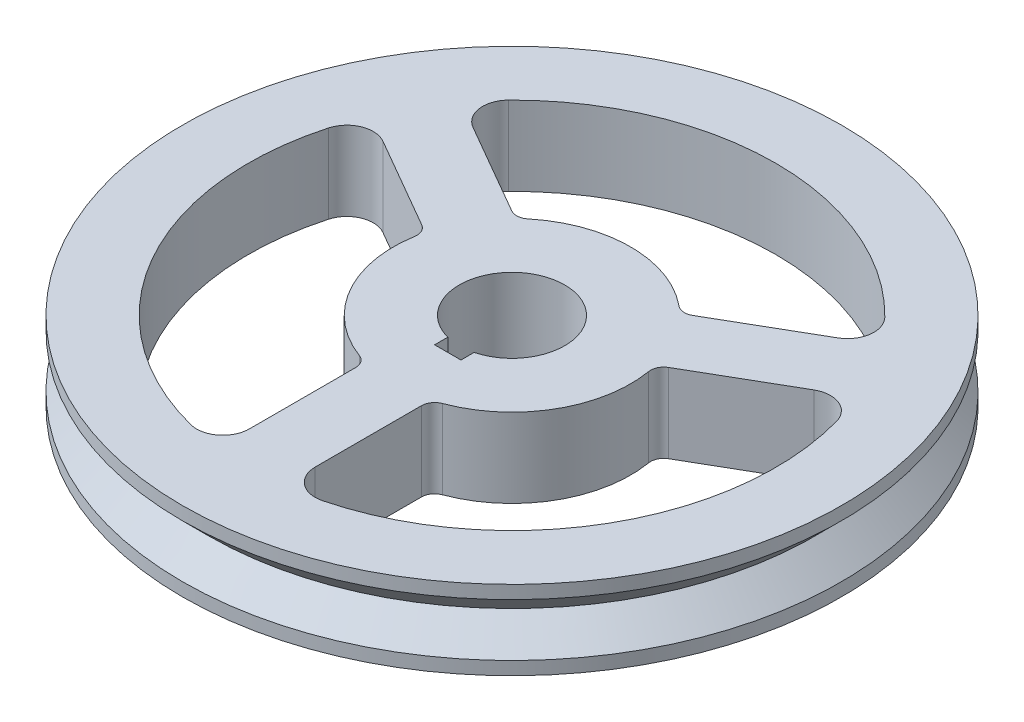
SolidWorks part; units mm, degrees
ref_plane "Front Plane" through (0, 0, 0) normal (0, 0, 1) x (1, 0, 0)
ref_plane "Top Plane" through (0, 0, 0) normal (0, 1, 0) x (1, 0, 0)
ref_plane "Right Plane" through (0, 0, 0) normal (1, 0, 0) x (0, 0, -1)
sketch "Sketch1" plane through (0, 0, 0) normal (0, 1, 0) x (1, 0, 0)
  line L0 (0, 185.3703) -> (0, -173.0817) construction
  line L1 (-213.9236, 0) -> (226.8817, 0) construction
  line L2 (34.3125, 34.2441) -> (69.2173, 54.3964)
  line L3 (0, 0) -> (-86.6025, 50) construction
  line L4 (-12.5, -46.8375) -> (-12.5, -87.1421)
  line L6 (-46.8125, 12.5934) -> (-81.7173, 32.7457)
  line L7 (-34.3125, 34.2441) -> (-69.2173, 54.3964)
  line L8 (12.5, -46.8375) -> (12.5, -87.1421)
  line L9 (46.8125, 12.5934) -> (81.7173, 32.7457)
  line L10 (-5, -19.3649) -> (-5, -24.3649)
  line L11 (5, -19.3649) -> (5, -24.3649)
  line L12 (-5, -24.3649) -> (5, -24.3649)
  circle A0 centre (0, 0) radius 125
  arc A1 (-96.3525, 26.7617) -> (-25, -96.8246) centre (0, 0) ccw
  arc A2 (-44.3812, 7.437) -> (-15.75, -42.1537) centre (0, 0) ccw
  arc A5 (-12.5, -87.1421) -> (-25, -96.8246) centre (-22.5, -87.1421) cw
  arc A6 (-81.7173, 32.7457) -> (-96.3525, 26.7617) centre (-86.7173, 24.0855) ccw
  arc A7 (-12.5, -46.8375) -> (-15.75, -42.1537) centre (-17.5, -46.8375) ccw
  arc A8 (-46.8125, 12.5934) -> (-44.3812, 7.437) centre (-49.3125, 8.2633) cw
  arc A9 (34.3125, 34.2441) -> (28.6312, 34.7168) centre (31.8125, 38.5742) cw
  arc A10 (69.2173, 54.3964) -> (71.3525, 70.0629) centre (64.2173, 63.0566) ccw
  arc A11 (71.3525, 70.0629) -> (-71.3525, 70.0629) centre (0, 0) ccw
  arc A12 (-69.2173, 54.3964) -> (-71.3525, 70.0629) centre (-64.2173, 63.0566) cw
  arc A13 (-34.3125, 34.2441) -> (-28.6312, 34.7168) centre (-31.8125, 38.5742) ccw
  arc A14 (28.6312, 34.7168) -> (-28.6312, 34.7168) centre (0, 0) ccw
  arc A15 (12.5, -46.8375) -> (15.75, -42.1537) centre (17.5, -46.8375) cw
  arc A16 (12.5, -87.1421) -> (25, -96.8246) centre (22.5, -87.1421) ccw
  arc A17 (25, -96.8246) -> (96.3525, 26.7617) centre (0, 0) ccw
  arc A18 (81.7173, 32.7457) -> (96.3525, 26.7617) centre (86.7173, 24.0855) cw
  arc A19 (46.8125, 12.5934) -> (44.3812, 7.437) centre (49.3125, 8.2633) ccw
  arc A20 (15.75, -42.1537) -> (44.3812, 7.437) centre (0, 0) ccw
  arc A21 (5, -19.3649) -> (-5, -19.3649) centre (0, 0) ccw
  point P17 (-12.5, -99.2157)
  point P22 (-92.1733, 38.7825)
  point P27 (-43.6874, 10.7892)
  point P49 (0, 0)
  dimension "D1" = 250
  dimension "D2" = 100
  dimension "D3" = 45
  dimension "D8" = 10
  dimension "D9" = 5
  dimension "D10" = 40
  dimension "D4" = 25
  dimension "D5" = 120
  dimension "D6" = 25
  dimension "D7" = 3
  dimension "D11" = 10
  dimension "D12" = 5
extrude "Boss-Extrude1" add sketch "Sketch1" along normal mid plane 30
sketch "Sketch2" plane through (0, 0, 0) normal (0, 0, 1) x (1, 0, 0)
  line L0 (-125, 10) -> (-125, -10)
  line L1 (-125, 10) -> (-115, 0)
  line L2 (-115, 0) -> (-125, -10)
  line L3 (125, 15) -> (-125, 15) construction
  line L4 (-125, -15) -> (125, -15) construction
  line L5 (0, 35.4267) -> (0, -44.7474) construction
  point P10 (-125, 0)
  dimension "D1" = 10
  dimension "D2" = 5
  dimension "D3" = 5
  dimension "D4" = 125
revolve "Cut-Revolve1" cut sketch "Sketch2" angle 360 about L5
